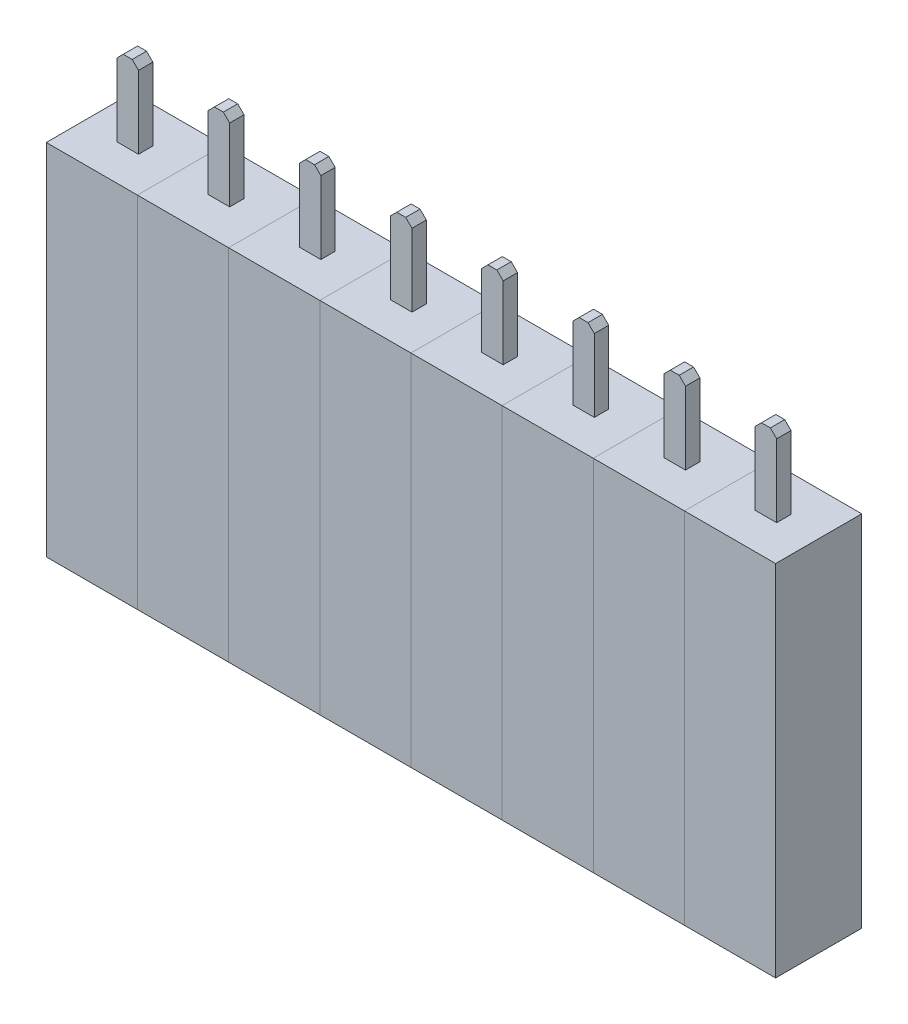
SolidWorks part; units mm, degrees
ref_plane "Front Plane" through (0, 0, 0) normal (0, 0, 1) x (1, 0, 0)
ref_plane "Top Plane" through (0, 0, 0) normal (0, 1, 0) x (1, 0, 0)
ref_plane "Right Plane" through (0, 0, 0) normal (1, 0, 0) x (0, 0, -1)
sketch "Sketch1" plane through (0, 0, 0) normal (0, 0, 1) x (1, 0, 0)
  line L1 (-1.27, 5) -> (1.27, 5)
  line L2 (-1.27, 5) -> (-1.27, -5)
  line L3 (-1.27, -5) -> (1.27, -5)
  line L4 (1.27, 5) -> (1.27, -5)
  line L5 (-1.27, 5) -> (1.27, -5) construction
  line L6 (-1.27, -5) -> (1.27, 5) construction
  point P0 (0, 0)
  dimension "D1" = 2.54
  dimension "D2" = 10
extrude "Boss-Extrude1" add sketch "Sketch1" along normal mid plane 2.4
sketch "Sketch2" plane through (0, -5, 0) normal (0, -1, 0) x (1, 0, 0)
  line L0 (0, -1.2) -> (0, 1.2) construction
  line L1 (-1.27, 1.2) -> (1.27, 1.2) construction
  line L2 (-1.27, -1.2) -> (1.27, -1.2) construction
  line L4 (-0.6, 0.6) -> (0.6, 0.6)
  line L5 (-0.6, 0.6) -> (-0.6, -0.6)
  line L6 (-0.6, -0.6) -> (0.6, -0.6)
  line L7 (0.6, 0.6) -> (0.6, -0.6)
  line L8 (-0.6, 0.6) -> (0.6, -0.6) construction
  line L9 (-0.6, -0.6) -> (0.6, 0.6) construction
  point P5 (0, 0)
  dimension "D1" = 1.2
extrude "Cut-Extrude1" cut sketch "Sketch2" against normal blind 7
sketch "Sketch3" plane through (0, 0, 0) normal (0, 0, 1) x (1, 0, 0)
  line L0 (-0.3, 5) -> (-0.3, 7.0243)
  line L1 (1.27, 5) -> (-1.27, 5) construction
  line L2 (-0.3, 7.0243) -> (-0.1243, 7.2)
  line L3 (-0.1243, 7.2) -> (0.1243, 7.2)
  line L4 (0, 7.2) -> (0, 5) construction
  line L5 (-0.3, 5) -> (0.3, 5)
  line L6 (0.3, 7.0243) -> (0.1243, 7.2)
  line L7 (0.3, 5) -> (0.3, 7.0243)
  dimension "D1" = 0.6
  dimension "D2" = 45
  dimension "D3" = 2.2
extrude "Boss-Extrude2" add sketch "Sketch3" along normal mid plane 0.4
pattern_linear "LPattern1" count 8 spacing 2.54 along (1, 0, 0) of bodies 103
